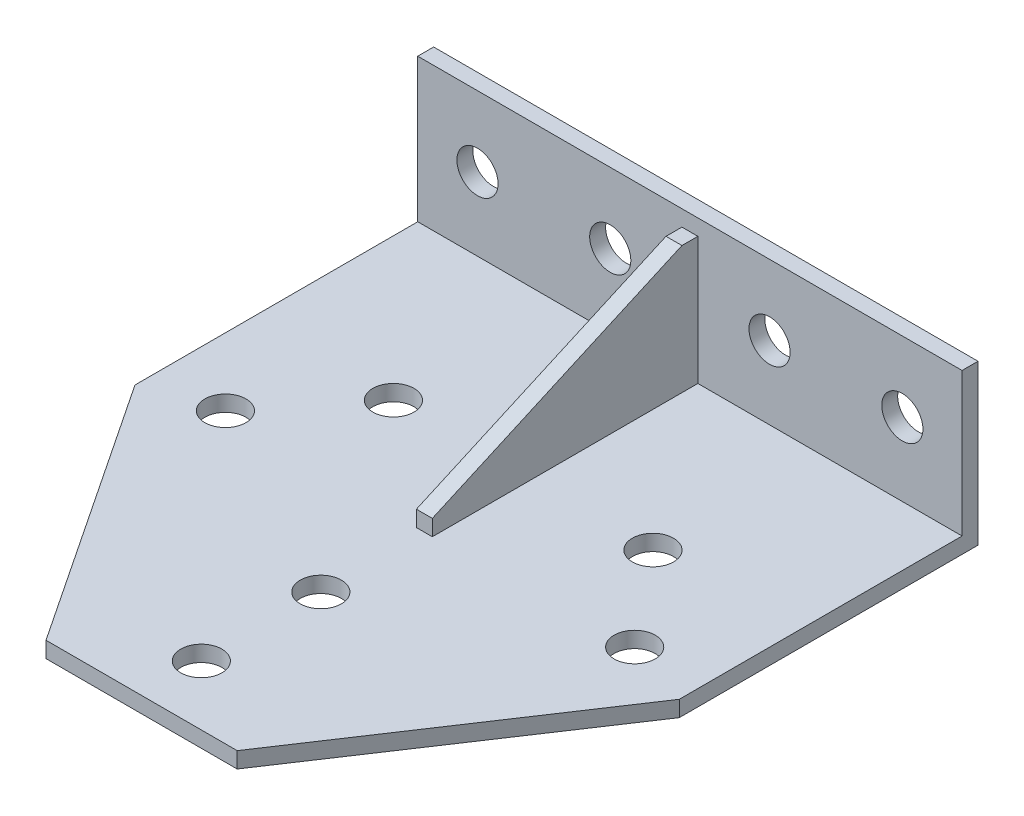
SolidWorks part; units mm, degrees
ref_plane "Front Plane" through (0, 0, 0) normal (0, 0, 1) x (1, 0, 0)
ref_plane "Top Plane" through (0, 0, 0) normal (0, 1, 0) x (1, 0, 0)
ref_plane "Right Plane" through (0, 0, 0) normal (1, 0, 0) x (0, 0, -1)
sketch "Sketch1" plane through (0, 0, 0) normal (0, 0, 1) x (1, 0, 0)
  line L1 (0, 0) -> (410, 0)
  line L2 (0, 0) -> (0, 120)
  line L3 (0, 120) -> (410, 120)
  line L4 (410, 0) -> (410, 120)
  circle A0 centre (45, 67) radius 15.5
  circle A1 centre (145, 67) radius 15.5
  circle A2 centre (265, 67) radius 15.5
  circle A3 centre (365, 67) radius 15.5
  dimension "D3" = 31
  dimension "D6" = 31
  dimension "D7" = 31
  dimension "D8" = 31
  dimension "D13" = 120
  dimension "D1" = 410
  dimension "D2" = 120
  dimension "D4" = 67
  dimension "D5" = 45
  dimension "D9" = 100
  dimension "D10" = 67
  dimension "D11" = 67
  dimension "D12" = 67
  dimension "D14" = 100
  dimension "D15" = 45
extrude "Extrude1" add sketch "Sketch1" along normal blind 12
sketch "Sketch2" plane through (0, 0, 12) normal (0, 0, 1) x (1, 0, 0)
  line L0 (410, 0) -> (410, 120) construction
  line L1 (0, 0) -> (410, 0)
  line L2 (0, 0) -> (0, 12)
  line L3 (0, 12) -> (410, 12)
  line L4 (410, 0) -> (410, 12)
  dimension "D1" = 12
extrude "Extrude2" add sketch "Sketch2" along normal blind 413
sketch "Sketch3" plane through (0, 12, 0) normal (0, 1, 0) x (1, 0, 0)
  line L0 (0, -425) -> (133, -425)
  line L1 (410, -425) -> (0, -425) construction
  line L2 (133, -425) -> (0, -225)
  line L3 (0, -425) -> (0, -12) construction
  line L4 (0, -225) -> (0, -425)
  line L5 (205, 0) -> (205, -425) construction
  line L6 (410, 0) -> (0, 0) construction
  line L7 (410, -425) -> (277, -425)
  line L8 (277, -425) -> (410, -225)
  line L9 (410, -225) -> (410, -425)
  line L10 (205, -16) -> (205, -2504) construction
  line L11 (205, -2504) -> (2205, -2504) construction
  line L12 (2205, -2504) -> (205, -16) construction
  circle A0 centre (302.7382, -137.5863) radius 15.5
  circle A1 centre (359.1257, -207.7323) radius 15.5
  circle A2 centre (107.2618, -137.5863) radius 15.5
  circle A3 centre (50.8743, -207.7323) radius 15.5
  circle A4 centre (205, -380) radius 15.5
  circle A5 centre (205, -290) radius 15.5
  dimension "D6" = 31
  dimension "D8" = 31
  dimension "D10" = 31
  dimension "D12" = 31
  dimension "D1" = 133
  dimension "D2" = 200
  dimension "D3" = 2000
  dimension "D4" = 2488
  dimension "D5" = 16
  dimension "D7" = 156
  dimension "D9" = 90
  dimension "D11" = 45
  dimension "D13" = 90
extrude "Extrude3" cut sketch "Sketch3" against normal blind 413
sketch "Sketch4" plane through (0, 0, 12) normal (0, 0, 1) x (1, 0, 0)
  line L0 (277, 12) -> (133, 12) construction
  line L1 (199, 108) -> (211, 108)
  line L2 (199, 108) -> (199, 12)
  line L3 (199, 12) -> (211, 12)
  line L4 (211, 108) -> (211, 12)
  line L5 (410, 120) -> (0, 120) construction
  line L6 (410, 12) -> (410, 120) construction
  dimension "D1" = 12
  dimension "D2" = 12
  dimension "D3" = 199
extrude "Extrude4" add sketch "Sketch4" along normal blind 200
sketch "Sketch5" plane through (199, 0, 0) normal (-1, 0, 0) x (0, 0, 1)
  line L0 (212, 108) -> (212, 24)
  line L1 (212, 108) -> (212, 12) construction
  line L2 (212, 24) -> (24, 108)
  line L3 (212, 108) -> (12, 108) construction
  line L4 (24, 108) -> (212, 108)
  dimension "D1" = 12
  dimension "D2" = 12
extrude "Extrude5" cut sketch "Sketch5" against normal blind 200
